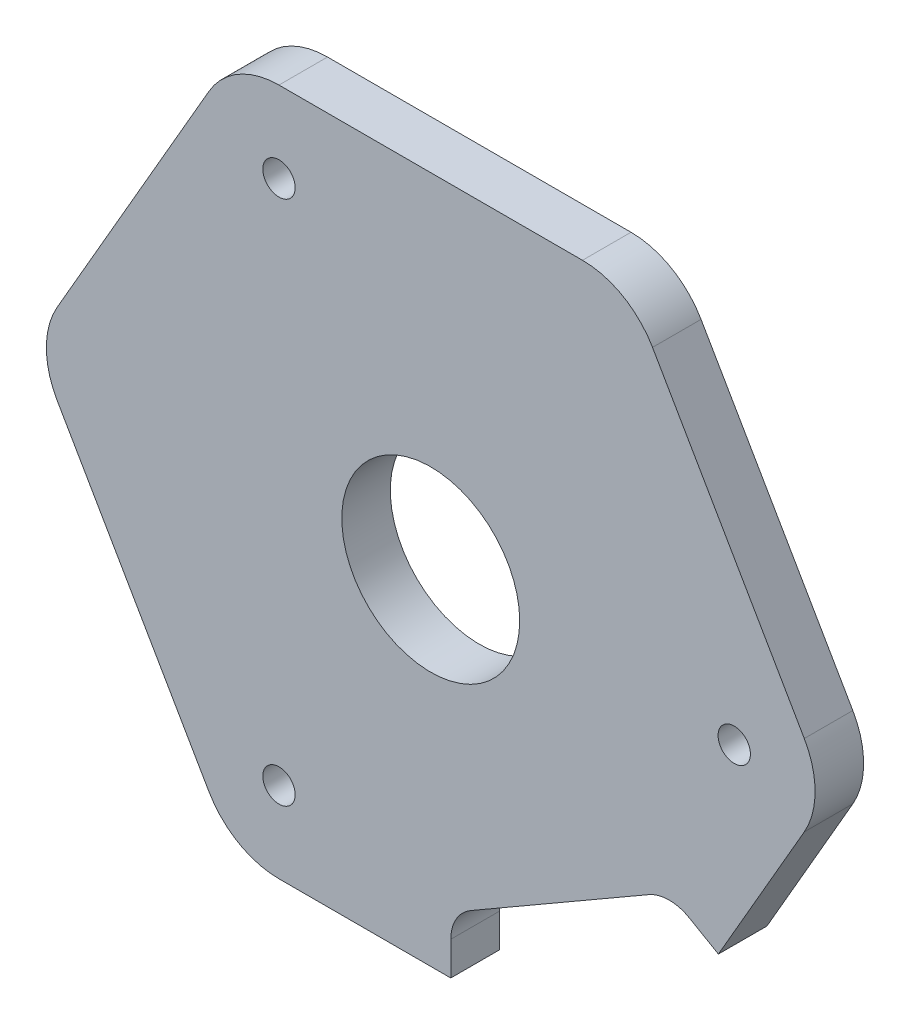
SolidWorks part; units mm, degrees
ref_plane "Front Plane" through (0, 0, 0) normal (0, 0, 1) x (1, 0, 0)
ref_plane "Top Plane" through (0, 0, 0) normal (0, 1, 0) x (1, 0, 0)
ref_plane "Right Plane" through (0, 0, 0) normal (1, 0, 0) x (0, 0, -1)
sketch "Sketch1" plane through (0, 0, 0) normal (0, 0, 1) x (1, 0, 0)
  line L9 (-57.7007, 162.3455) -> (-95.2285, 162.3455)
  line L10 (-30.2766, 124.8455) -> (-49.0405, 157.3455)
  line L11 (-40.897, 96.4504) -> (-30.2766, 114.8455)
  line L12 (-44.4877, 98.5235) -> (-40.897, 96.4504)
  line L13 (-71.4877, 85.8218) -> (-49.4877, 98.5235)
  line L14 (-73.9877, 77.3455) -> (-73.9877, 81.4917)
  line L15 (-95.2285, 77.3455) -> (-73.9877, 77.3455)
  line L16 (-122.6526, 114.8455) -> (-103.8888, 82.3455)
  line L17 (-103.8888, 157.3455) -> (-122.6526, 124.8455)
  circle A11 centre (-38.9369, 119.8455) radius 2
  circle A12 centre (-95.2285, 87.3455) radius 2
  circle A13 centre (-76.4646, 119.8455) radius 11
  circle A14 centre (-95.2285, 152.3455) radius 2
  arc A15 (-95.2285, 162.3455) -> (-103.8888, 157.3455) centre (-95.2285, 152.3455) ccw
  arc A16 (-49.0405, 157.3455) -> (-57.7007, 162.3455) centre (-57.7007, 152.3455) ccw
  arc A17 (-30.2766, 114.8455) -> (-30.2766, 124.8455) centre (-38.9369, 119.8455) ccw
  arc A18 (-44.4877, 98.5235) -> (-49.4877, 98.5235) centre (-46.9877, 94.1934) ccw
  arc A19 (-71.4877, 85.8218) -> (-73.9877, 81.4917) centre (-68.9877, 81.4917) ccw
  arc A20 (-103.8888, 82.3455) -> (-95.2285, 77.3455) centre (-95.2285, 87.3455) ccw
  arc A21 (-122.6526, 124.8455) -> (-122.6526, 114.8455) centre (-113.9924, 119.8455) ccw
  point P1 (0, 0)
  point P3 (0, 0)
  point P5 (-45.2075, 115.5312)
  point P7 (0, 0)
  point P26 (-104.77, 95.0359)
  point P29 (-46.8951, 117.0605)
  dimension "D4" = 4
  dimension "D8" = 65
  dimension "D9" = 5
  dimension "D10" = 5
  dimension "D3" = 10
  dimension "D15" = 22
  dimension "D1" = 37.5278
  dimension "D2" = 21.2408
  dimension "D5" = 25.4034
  dimension "D6" = 77.3455
  dimension "D7" = 90
  dimension "D11" = 65
  dimension "D12" = 65
  dimension "D13" = 10
  dimension "D14" = 10
  dimension "D16" = 37.5278
  dimension "D17" = 37.5278
  dimension "D18" = 83.6431
  dimension "D19" = 90
  dimension "D20" = 60
  dimension "D21" = 60
  dimension "D22" = 60
  dimension "D23" = 60
  dimension "D24" = 60
  dimension "D25" = 60
  dimension "D26" = 10
  dimension "D27" = 114.8455
extrude "Boss-Extrude1" add sketch "Sketch1" along normal blind 6 separate body
